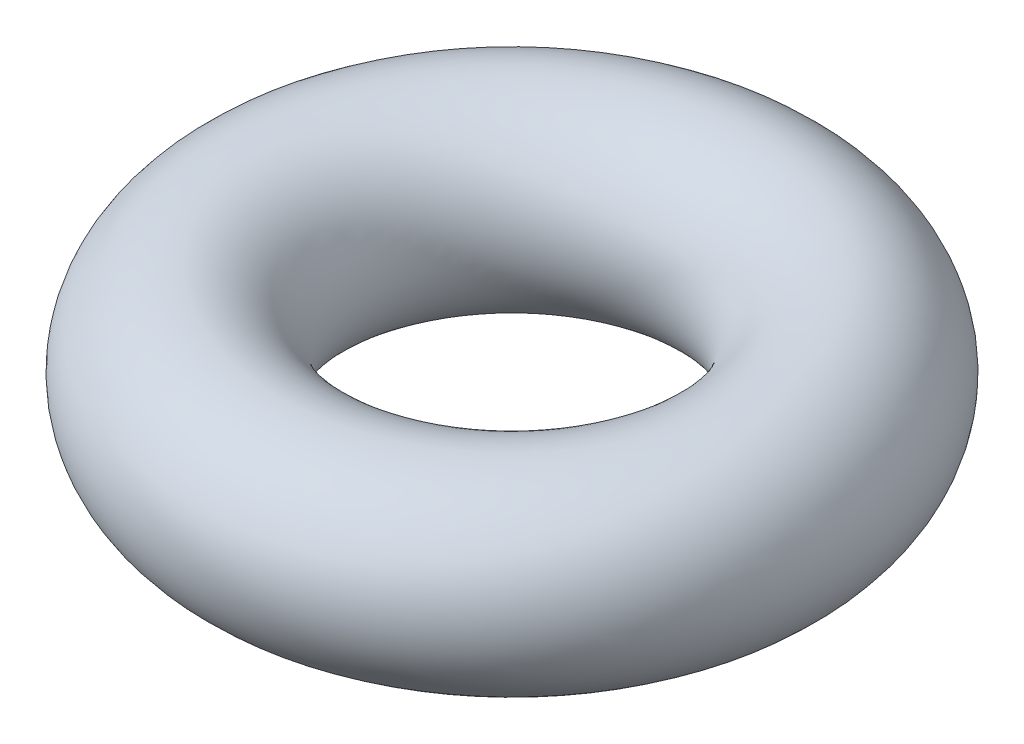
SolidWorks part; units mm, degrees
ref_plane "Front Plane" through (0, 0, 0) normal (0, 0, 1) x (1, 0, 0)
ref_plane "Top Plane" through (0, 0, 0) normal (0, 1, 0) x (1, 0, 0)
ref_plane "Right Plane" through (0, 0, 0) normal (1, 0, 0) x (0, 0, -1)
sketch "Sketch1" plane through (0, 0, 0) normal (0, 0, 1) x (1, 0, 0)
  line L0 (63.5, 33.2863) -> (63.5, -30.7258)
  circle A0 centre (0, 0) radius 23.8125
  circle A1 centre (0, 0) radius 25.4
  dimension "D1" = 50.8
  dimension "D2" = 47.625
  dimension "D3" = 63.5
revolve "Revolve2" add sketch "Sketch1" angle 360 about L0
